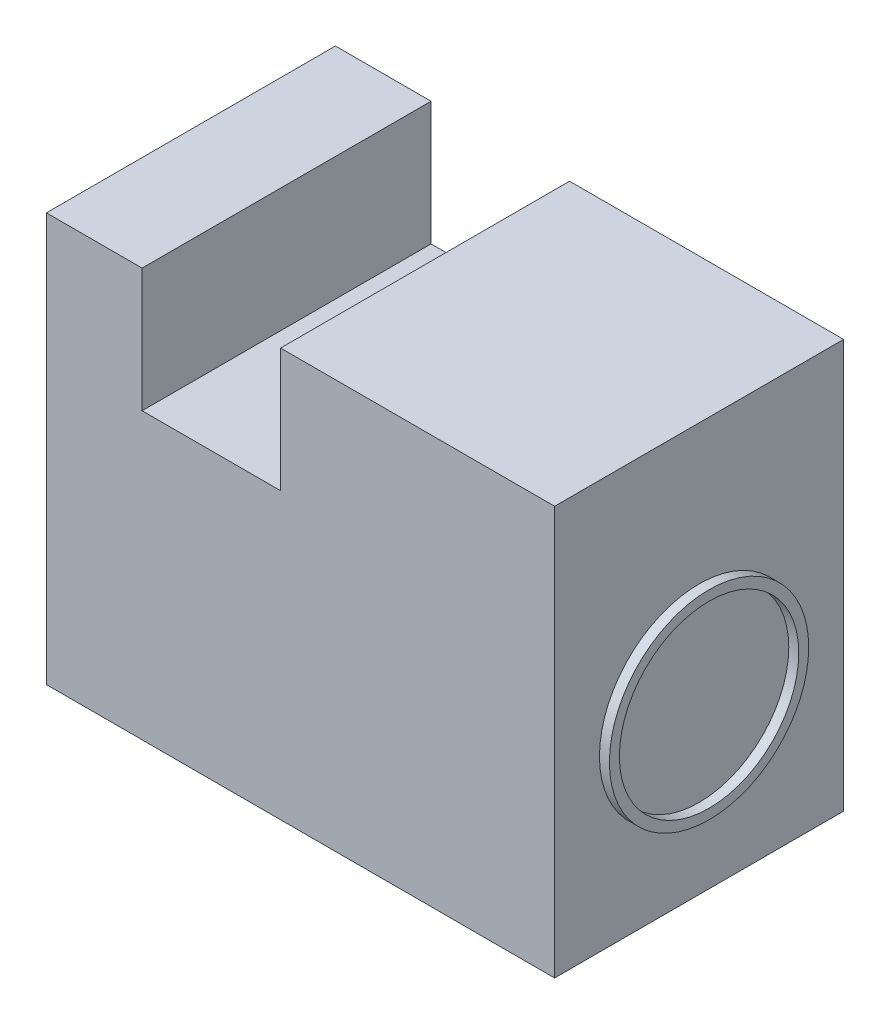
SolidWorks part; units mm, degrees
ref_plane "Front Plane" through (0, 0, 0) normal (0, 0, 1) x (1, 0, 0)
ref_plane "Top Plane" through (0, 0, 0) normal (0, 1, 0) x (1, 0, 0)
ref_plane "Right Plane" through (0, 0, 0) normal (1, 0, 0) x (0, 0, -1)
sketch "Sketch1" plane through (0, 0, 0) normal (0, 1, 0) x (1, 0, 0)
  line L1 (-25.5, -14.5) -> (25.5, -14.5)
  line L2 (-25.5, -14.5) -> (-25.5, 14.5)
  line L3 (-25.5, 14.5) -> (25.5, 14.5)
  line L4 (25.5, -14.5) -> (25.5, 14.5)
  line L5 (-25.5, -14.5) -> (25.5, 14.5) construction
  line L6 (-25.5, 14.5) -> (25.5, -14.5) construction
  point P0 (0, 0)
  dimension "D1" = 51
  dimension "D2" = 29
extrude "Boss-Extrude1" add sketch "Sketch1" along normal blind 41
sketch "Sketch2" plane through (25.5, 0, 0) normal (1, 0, 0) x (0, 0, -1)
  line L0 (-14.5, 0) -> (14.5, 0) construction
  line L1 (14.5, 41) -> (14.5, 0) construction
  circle A0 centre (0, 17) radius 10
  circle A1 centre (0, 17) radius 9
  dimension "D1" = 17
  dimension "D2" = 20
  dimension "D4" = 1
  dimension "D3" = 14.5
extrude "Boss-Extrude2" add sketch "Sketch2" along normal blind 1
sketch "Sketch3" plane through (0, 0, 14.5) normal (0, 0, 1) x (1, 0, 0)
  line L0 (-25.5, 41) -> (25.5, 41) construction
  line L1 (-15.9, 41) -> (-2, 41)
  line L2 (-15.9, 41) -> (-15.9, 28.6)
  line L3 (-15.9, 28.6) -> (-2, 28.6)
  line L4 (-2, 41) -> (-2, 28.6)
  line L5 (-25.5, 41) -> (-25.5, 0) construction
  dimension "D1" = 9.6
  dimension "D2" = 13.9
  dimension "D3" = 12.4
extrude "Cut-Extrude1" cut sketch "Sketch3" against normal through all
sketch "Sketch4" plane through (0, 0, -14.5) normal (0, 0, -1) x (-1, 0, 0)
  line L0 (-25.5, 41) -> (2, 41) construction
  line L1 (-25.5, 41) -> (-25.5, 0) construction
  line L2 (-25.5, 0) -> (25.5, 0) construction
  line L3 (25.5, 41) -> (25.5, 0) construction
  circle A0 centre (-18.5, 34) radius 1.5
  circle A1 centre (18.5, 7) radius 1.5
  dimension "D3" = 7
  dimension "D5" = 3
  dimension "D1" = 7
  dimension "D2" = 7
  dimension "D4" = 7
extrude "Cut-Extrude2" cut sketch "Sketch4" against normal blind 5
